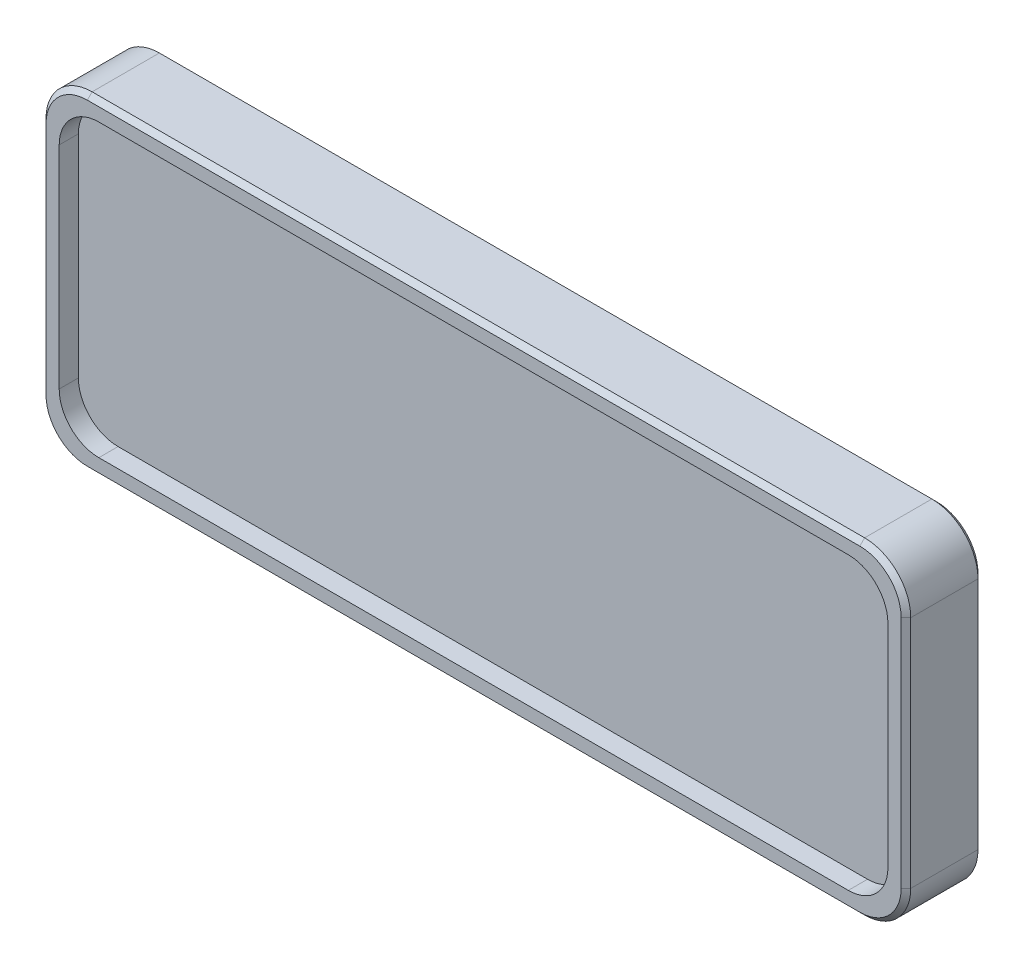
SolidWorks part; units mm, degrees
ref_plane "Front Plane" through (0, 0, 0) normal (0, 0, 1) x (1, 0, 0)
ref_plane "Top Plane" through (0, 0, 0) normal (0, 1, 0) x (1, 0, 0)
ref_plane "Right Plane" through (0, 0, 0) normal (1, 0, 0) x (0, 0, -1)
sketch "Sketch1" plane through (0, 0, 0) normal (0, 0, 1) x (1, 0, 0)
  line L0 (71.4375, -19.3675) -> (71.4375, 19.3675)
  line L1 (-69.85, -25.4) -> (69.85, -25.4) construction
  line L2 (-69.85, -25.4) -> (-69.85, 25.4) construction
  line L3 (-69.85, 25.4) -> (69.85, 25.4) construction
  line L4 (69.85, -25.4) -> (69.85, 25.4) construction
  line L5 (-69.85, -25.4) -> (69.85, 25.4) construction
  line L6 (-69.85, 25.4) -> (69.85, -25.4) construction
  line L7 (-63.8175, 26.9875) -> (63.8175, 26.9875)
  line L8 (-71.4375, -19.3675) -> (-71.4375, 19.3675)
  line L9 (-63.8175, -26.9875) -> (63.8175, -26.9875)
  line L10 (-71.4375, 26.9875) -> (71.4375, 26.9875) construction
  line L11 (-71.4375, -26.9875) -> (-71.4375, 26.9875) construction
  line L12 (-71.4375, -26.9875) -> (71.4375, -26.9875) construction
  line L13 (71.4375, -26.9875) -> (71.4375, 26.9875) construction
  arc A0 (-63.8175, 26.9875) -> (-71.4375, 19.3675) centre (-63.8175, 19.3675) ccw
  arc A1 (-71.4375, -19.3675) -> (-63.8175, -26.9875) centre (-63.8175, -19.3675) ccw
  arc A2 (71.4375, -19.3675) -> (63.8175, -26.9875) centre (63.8175, -19.3675) cw
  arc A3 (71.4375, 19.3675) -> (63.8175, 26.9875) centre (63.8175, 19.3675) ccw
  point P0 (0, 0)
  dimension "D4" = 7.62
  dimension "D1" = 50.8
  dimension "D2" = 139.7
  dimension "D3" = 1.5875
extrude "Boss-Extrude1" add sketch "Sketch1" against normal blind 12.7
sketch "Sketch2" plane through (0, 0, 0) normal (0, 0, 1) x (1, 0, 0)
  line L4 (-71.4375, 19.3675) -> (-71.4375, -19.3675)
  line L5 (-63.8175, -26.9875) -> (63.8175, -26.9875)
  line L6 (71.4375, -19.3675) -> (71.4375, 19.3675)
  line L7 (63.8175, 26.9875) -> (-63.8175, 26.9875)
  line L8 (-71.4375, 19.3675) -> (-71.4375, -19.3675) construction
  line L9 (-63.8175, -26.9875) -> (63.8175, -26.9875) construction
  line L10 (71.4375, -19.3675) -> (71.4375, 19.3675) construction
  line L11 (63.8175, 26.9875) -> (-63.8175, 26.9875) construction
  line L16 (68.4625, -17.4625) -> (68.4625, 17.4625)
  line L17 (61.9125, 24.0125) -> (-61.9125, 24.0125)
  line L18 (-68.4625, 17.4625) -> (-68.4625, -17.4625)
  line L19 (-61.9125, -24.0125) -> (61.9125, -24.0125)
  line L20 (68.4625, -17.4625) -> (68.4625, 17.4625)
  line L21 (61.9125, 24.0125) -> (-61.9125, 24.0125)
  line L22 (-68.4625, 17.4625) -> (-68.4625, -17.4625)
  line L23 (-61.9125, -24.0125) -> (61.9125, -24.0125)
  arc A4 (-63.8175, 26.9875) -> (-71.4375, 19.3675) centre (-63.8175, 19.3675) ccw
  arc A5 (-71.4375, -19.3675) -> (-63.8175, -26.9875) centre (-63.8175, -19.3675) ccw
  arc A6 (63.8175, -26.9875) -> (71.4375, -19.3675) centre (63.8175, -19.3675) ccw
  arc A7 (71.4375, 19.3675) -> (63.8175, 26.9875) centre (63.8175, 19.3675) ccw
  arc A8 (-63.8175, 26.9875) -> (-71.4375, 19.3675) centre (-63.8175, 19.3675) ccw construction
  arc A9 (-71.4375, -19.3675) -> (-63.8175, -26.9875) centre (-63.8175, -19.3675) ccw construction
  arc A10 (63.8175, -26.9875) -> (71.4375, -19.3675) centre (63.8175, -19.3675) ccw construction
  arc A11 (71.4375, 19.3675) -> (63.8175, 26.9875) centre (63.8175, 19.3675) ccw construction
  arc A16 (68.4625, 17.4625) -> (61.9125, 24.0125) centre (61.9125, 17.4625) ccw
  arc A17 (-61.9125, 24.0125) -> (-68.4625, 17.4625) centre (-61.9125, 17.4625) ccw
  arc A18 (-68.4625, -17.4625) -> (-61.9125, -24.0125) centre (-61.9125, -17.4625) ccw
  arc A19 (61.9125, -24.0125) -> (68.4625, -17.4625) centre (61.9125, -17.4625) ccw
  arc A20 (68.4625, 17.4625) -> (61.9125, 24.0125) centre (61.9125, 17.4625) ccw
  arc A21 (-61.9125, 24.0125) -> (-68.4625, 17.4625) centre (-61.9125, 17.4625) ccw
  arc A22 (-68.4625, -17.4625) -> (-61.9125, -24.0125) centre (-61.9125, -17.4625) ccw
  arc A23 (61.9125, -24.0125) -> (68.4625, -17.4625) centre (61.9125, -17.4625) ccw
  dimension "D1" = 0
  dimension "D2" = 0.2
extrude "Cut-Extrude1" cut sketch "Sketch2" against normal blind 3.175
sketch "Sketch3" plane through (0, -26.9875, 0) normal (0, -1, 0) x (1, 0, 0)
  line L0 (0, -12.7) -> (0, 0) construction
  line L1 (-63.8175, -12.7) -> (63.8175, -12.7) construction
  line L2 (-63.8175, 0) -> (63.8175, 0) construction
  circle A0 centre (0, -6.35) radius 2.8575
  dimension "D1" = 5.715
extrude "Cut-Extrude2" cut sketch "Sketch3" against normal blind 25.4
sketch "Sketch4" plane through (0, -26.9875, 0) normal (0, -1, 0) x (1, 0, 0)
  circle A0 centre (0, -6.35) radius 3.175 construction
  circle A1 centre (0, -6.35) radius 3.5719
  dimension "D1" = 0.3969
extrude "Cut-Extrude4" cut sketch "Sketch4" against normal blind 2.54
chamfer "Chamfer1" distance 0.7937 angle 45 16 edges at (0, 26.9875, -12.7) (-69.2057, 24.7557, -12.7) (69.2057, 24.7557, -12.7) (-71.4375, 0, -12.7) (71.4375, 0, -12.7) (-69.2057, -24.7557, -12.7) (69.2057, -24.7557, -12.7) (0, -26.9875, -12.7) (0, 26.9875, 0) (-69.2057, 24.7557, 0) (69.2057, 24.7557, 0) (-71.4375, 0, 0) (71.4375, 0, 0) (-69.2057, -24.7557, 0) (69.2057, -24.7557, 0) (0, -26.9875, 0)
